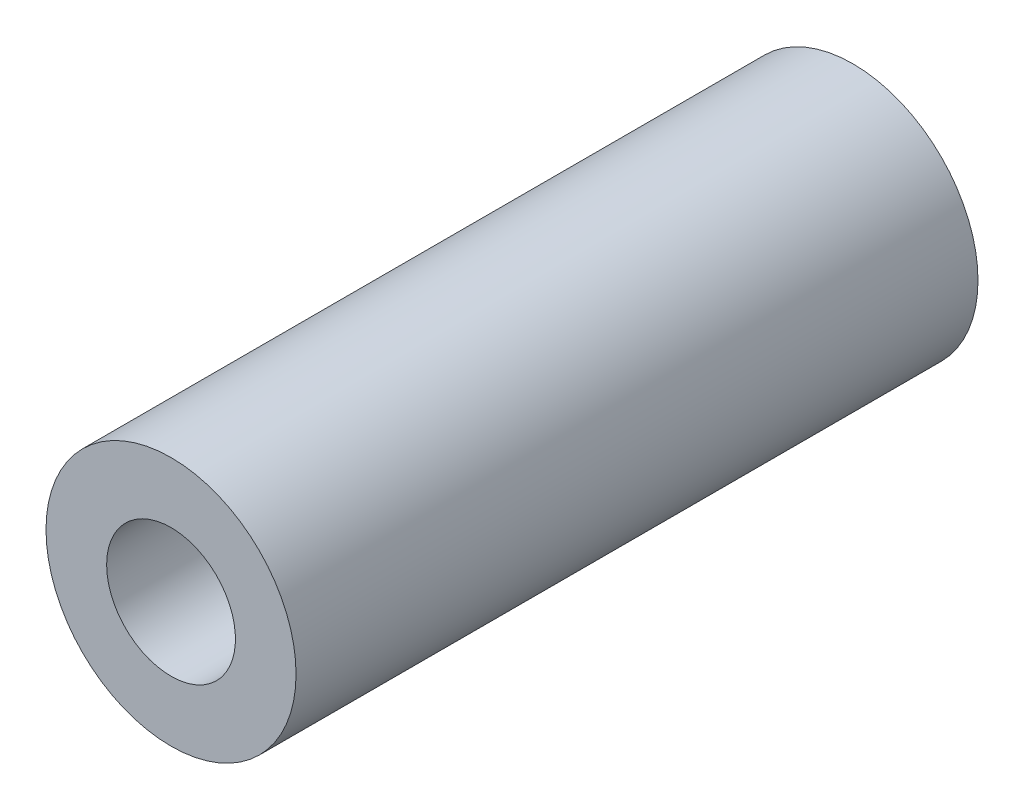
SolidWorks part; units mm, degrees
material "AISI 304"
ref_plane "Plano frontal" through (0, 0, 0) normal (0, 0, 1) x (1, 0, 0)
ref_plane "Plano superior" through (0, 0, 0) normal (0, 1, 0) x (1, 0, 0)
ref_plane "Plano direito" through (0, 0, 0) normal (1, 0, 0) x (0, 0, -1)
sketch "Esboço1" plane through (0, 0, 0) normal (0, 0, 1) x (1, 0, 0)
  circle A0 centre (0, 0) radius 4.25
  circle A1 centre (0, 0) radius 8.25
  dimension "D1" = 8.5
  dimension "D2" = 16.5
extrude "Ressalto-extrusão1" add sketch "Esboço1" along normal mid plane 45
